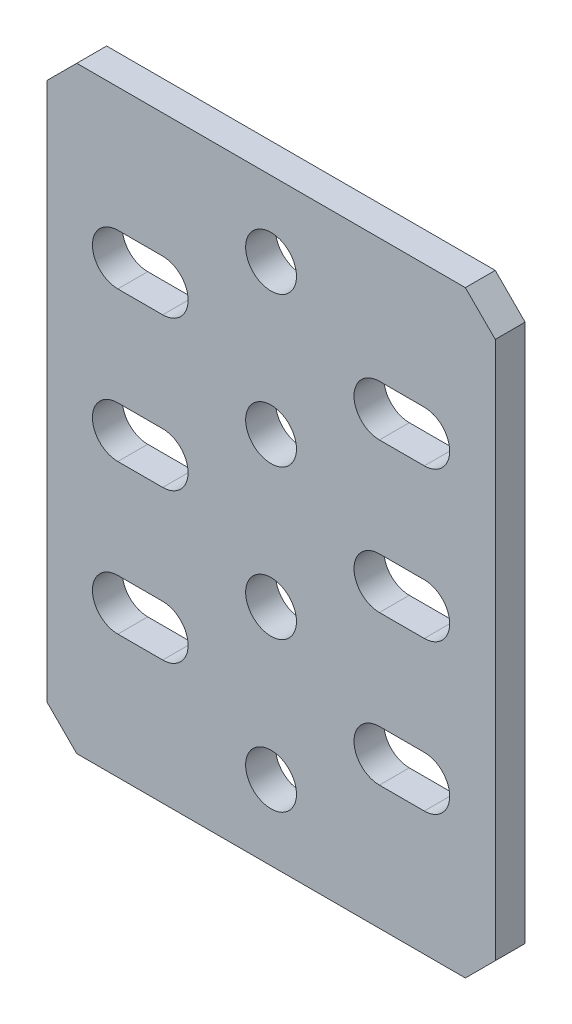
SolidWorks part; units mm, degrees
ref_plane "Front Plane" through (0, 0, 0) normal (0, 0, 1) x (1, 0, 0)
ref_plane "Top Plane" through (0, 0, 0) normal (0, 1, 0) x (1, 0, 0)
ref_plane "Right Plane" through (0, 0, 0) normal (1, 0, 0) x (0, 0, -1)
ref_plane "Plane1" through (0, 0, 0) normal (0, 0, -1) x (-1, 0, 0)
sketch "Sketch1" plane through (0, 0, 0) normal (0, 0, -1) x (-1, 0, 0)
  line L0 (-10.25, -8.3) -> (-7.25, -8.3)
  line L1 (-7.25, -11.7) -> (-10.25, -11.7)
  line L2 (7.25, -8.3) -> (10.25, -8.3)
  line L3 (10.25, -11.7) -> (7.25, -11.7)
  line L4 (-10.25, 1.7) -> (-7.25, 1.7)
  line L5 (-7.25, -1.7) -> (-10.25, -1.7)
  line L6 (7.25, 1.7) -> (10.25, 1.7)
  line L7 (10.25, -1.7) -> (7.25, -1.7)
  line L8 (13, -20) -> (15, -18)
  line L9 (15, -18) -> (15, 18)
  line L10 (15, 18) -> (13, 20)
  line L11 (13, 20) -> (-13, 20)
  line L12 (-13, 20) -> (-15, 18)
  line L13 (-15, 18) -> (-15, -18)
  line L14 (-15, -18) -> (-13, -20)
  line L15 (-13, -20) -> (13, -20)
  line L16 (10.25, 8.3) -> (7.25, 8.3)
  line L17 (7.25, 11.7) -> (10.25, 11.7)
  line L18 (-7.25, 8.3) -> (-10.25, 8.3)
  line L19 (-10.25, 11.7) -> (-7.25, 11.7)
  circle A0 centre (0, -15) radius 1.7
  circle A1 centre (0, -5) radius 1.7
  arc A2 (-10.25, -11.7) -> (-10.25, -8.3) centre (-10.25, -10) cw
  arc A3 (-7.25, -8.3) -> (-7.25, -11.7) centre (-7.25, -10) cw
  arc A4 (7.25, -11.7) -> (7.25, -8.3) centre (7.25, -10) cw
  arc A5 (10.25, -8.3) -> (10.25, -11.7) centre (10.25, -10) cw
  arc A6 (-10.25, -1.7) -> (-10.25, 1.7) centre (-10.25, 0) cw
  arc A7 (-7.25, 1.7) -> (-7.25, -1.7) centre (-7.25, 0) cw
  arc A8 (7.25, -1.7) -> (7.25, 1.7) centre (7.25, 0) cw
  arc A9 (10.25, 1.7) -> (10.25, -1.7) centre (10.25, 0) cw
  arc A10 (7.25, 8.3) -> (7.25, 11.7) centre (7.25, 10) cw
  arc A11 (10.25, 11.7) -> (10.25, 8.3) centre (10.25, 10) cw
  arc A12 (-10.25, 8.3) -> (-10.25, 11.7) centre (-10.25, 10) cw
  arc A13 (-7.25, 11.7) -> (-7.25, 8.3) centre (-7.25, 10) cw
  circle A14 centre (0, 15) radius 1.7
  circle A15 centre (0, 5) radius 1.7
extrude "Boss-Extrude1" add sketch "Sketch1" against normal blind 2
